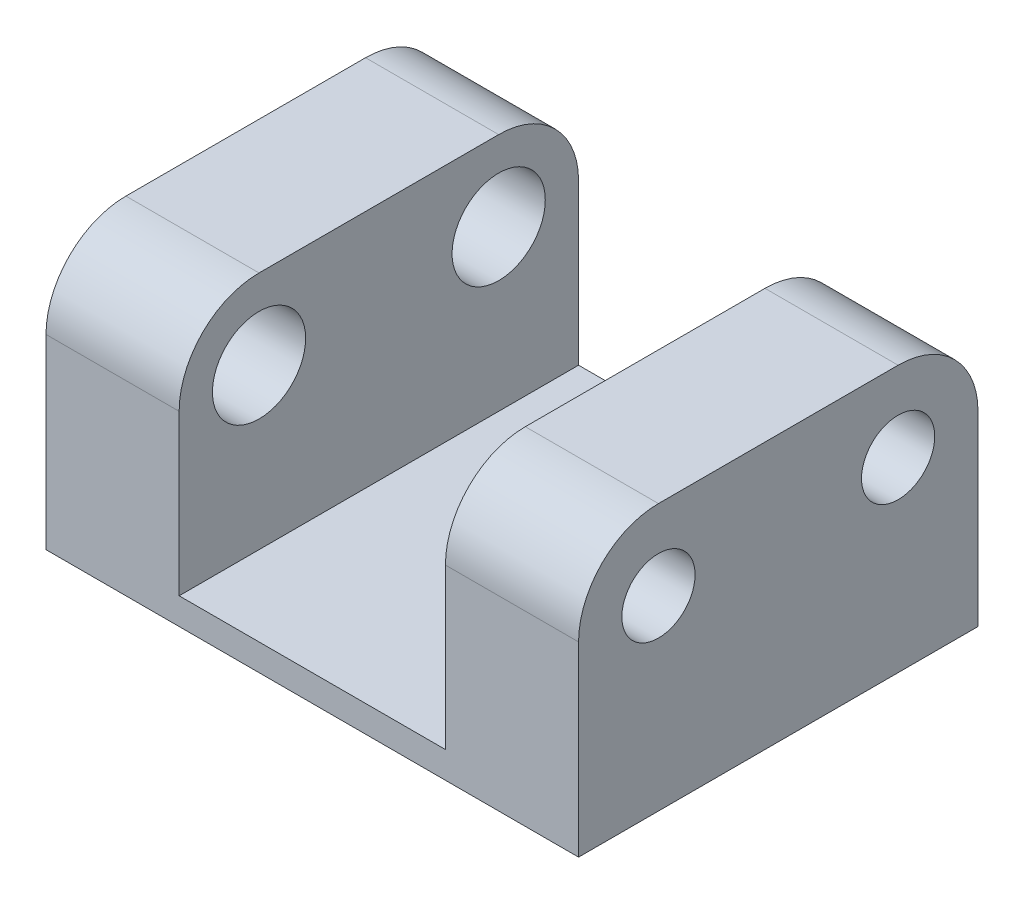
SolidWorks part; units mm, degrees
ref_plane "Front Plane" through (0, 0, 0) normal (0, 0, 1) x (1, 0, 0)
ref_plane "Top Plane" through (0, 0, 0) normal (0, 1, 0) x (1, 0, 0)
ref_plane "Right Plane" through (0, 0, 0) normal (1, 0, 0) x (0, 0, -1)
sketch "Sketch1" plane through (0, 0, 0) normal (0, 0, 1) x (1, 0, 0)
  line L0 (0, 0) -> (-20, 0)
  line L1 (-20, 0) -> (-20, 20)
  line L2 (-20, 20) -> (-10, 20)
  line L3 (-10, 20) -> (-10, 2)
  line L4 (-10, 2) -> (10, 2)
  line L5 (10, 2) -> (10, 20)
  line L6 (10, 20) -> (20, 20)
  line L7 (20, 20) -> (20, 0)
  line L8 (20, 0) -> (0, 0)
  point P6 (0, 2)
  dimension "D1" = 20
  dimension "D2" = 10
  dimension "D3" = 10
  dimension "D4" = 20
  dimension "D5" = 18
extrude "Boss-Extrude1" add sketch "Sketch1" along normal blind 30
fillet "Fillet1" radius 6 4 edges at (15, 20, 30) (-15, 20, 30) (-15, 20, 0) (15, 20, 0)
sketch "Sketch2" plane through (0, 0, 0) normal (1, 0, 0) x (0, 0, -1)
  line L0 (-24, 14) -> (-6, 14) construction
  line L1 (-15, 20) -> (-15, 0) construction
  line L2 (-24, 20) -> (-6, 20) construction
  line L3 (-30, 0) -> (0, 0) construction
  line L4 (-6, 20) -> (-6, 14) construction
  line L5 (-6, 14) -> (0, 14) construction
  circle A0 centre (-24, 14) radius 3.5
  circle A1 centre (-6, 14) radius 3.5
  point P10 (-15, 14)
  dimension "D1" = 7
  dimension "D2" = 7
extrude "Cut-Extrude1" cut sketch "Sketch2" against normal blind 30
sketch "Sketch3" plane through (0, 0, 0) normal (1, 0, 0) x (0, 0, -1)
  circle A0 centre (-6, 14) radius 2.75
  circle A1 centre (-24, 14) radius 2.75
  dimension "D1" = 5.5
  dimension "D2" = 5.5
extrude "Cut-Extrude2" cut sketch "Sketch3" along normal blind 30
